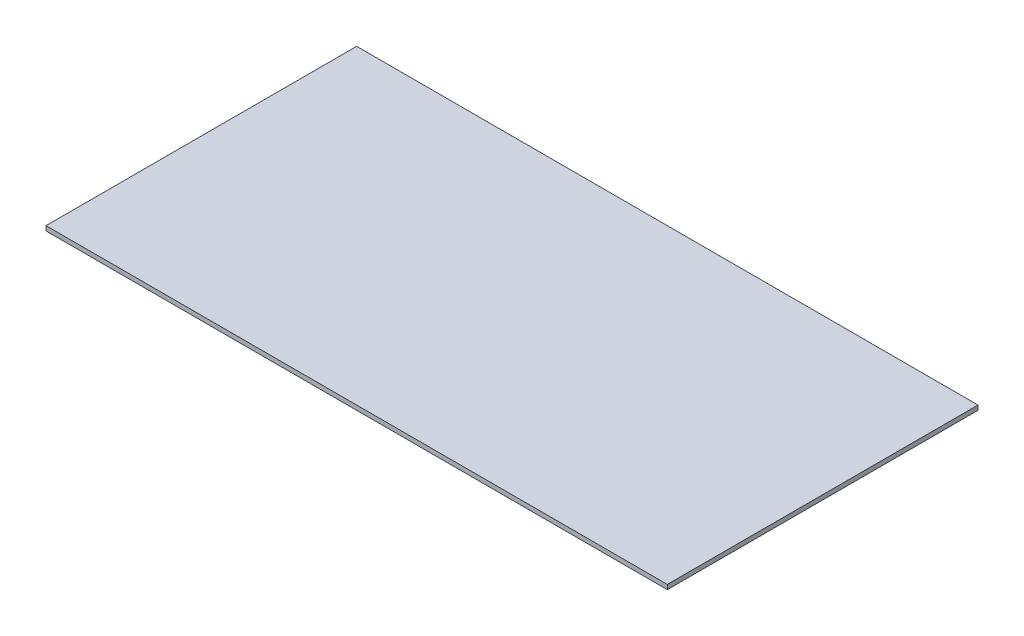
SolidWorks part; units mm, degrees
ref_plane "Front Plane" through (0, 0, 0) normal (0, 0, 1) x (1, 0, 0)
ref_plane "Top Plane" through (0, 0, 0) normal (0, 1, 0) x (1, 0, 0)
ref_plane "Right Plane" through (0, 0, 0) normal (1, 0, 0) x (0, 0, -1)
sketch "Sketch1" plane through (0, 0, 0) normal (0, 1, 0) x (1, 0, 0)
  line L1 (-50.9, 25.45) -> (50.9, 25.45)
  line L2 (-50.9, 25.45) -> (-50.9, -25.45)
  line L3 (-50.9, -25.45) -> (50.9, -25.45)
  line L4 (50.9, 25.45) -> (50.9, -25.45)
  line L5 (-50.9, 25.45) -> (50.9, -25.45) construction
  line L6 (-50.9, -25.45) -> (50.9, 25.45) construction
  point P4 (0, 0)
  point P5 (0, 0)
  dimension "D1" = 101.8
  dimension "D2" = 50.9
extrude "Boss-Extrude1" add sketch "Sketch1" along normal blind 0.75
